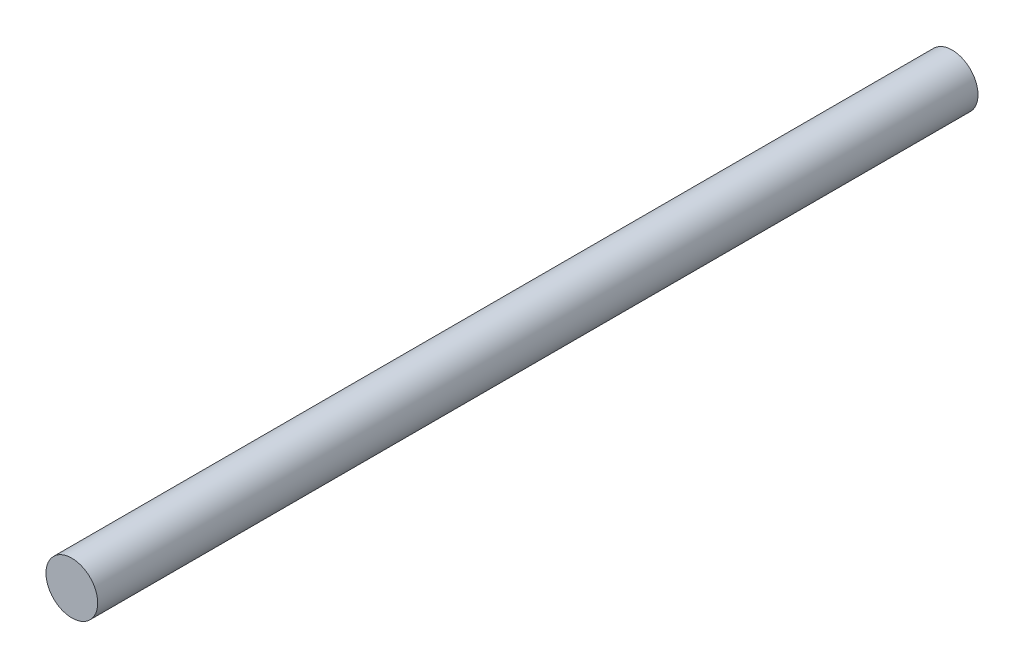
SolidWorks part; units mm, degrees
ref_plane "Front Plane" through (0, 0, 0) normal (0, 0, 1) x (1, 0, 0)
ref_plane "Top Plane" through (0, 0, 0) normal (0, 1, 0) x (1, 0, 0)
ref_plane "Right Plane" through (0, 0, 0) normal (1, 0, 0) x (0, 0, -1)
other "Default"
sketch "Sketch1" plane through (0, 0, 0) normal (0, 0, 1) x (1, 0, 0)
  circle A0 centre (0, 0) radius 2.5
  dimension "Diameter" = 5
extrude "Boss-Extrude1" add sketch "Sketch1" along normal mid plane 85
